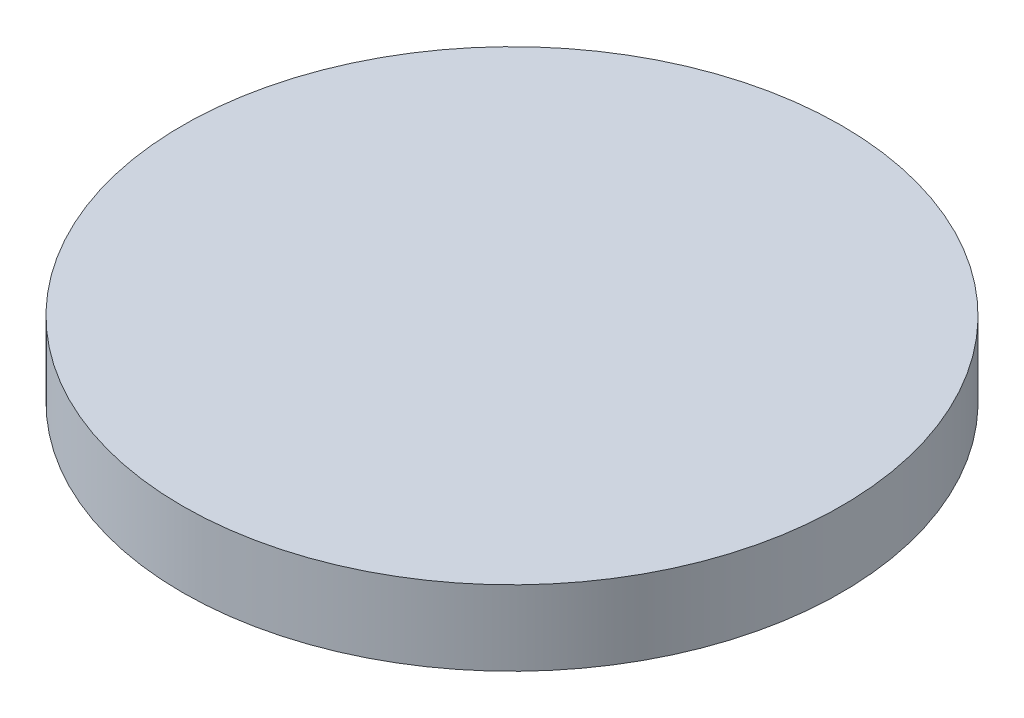
SolidWorks part; units mm, degrees
ref_plane "Front Plane" through (0, 0, 0) normal (0, 0, 1) x (1, 0, 0)
ref_plane "Top Plane" through (0, 0, 0) normal (0, 1, 0) x (1, 0, 0)
ref_plane "Right Plane" through (0, 0, 0) normal (1, 0, 0) x (0, 0, -1)
sketch "Sketch1" plane through (0, 0, 0) normal (0, 1, 0) x (1, 0, 0)
  circle A0 centre (0, 0) radius 13.97
  dimension "D1" = 27.94
extrude "Boss-Extrude1" add sketch "Sketch1" along normal blind 3.175
